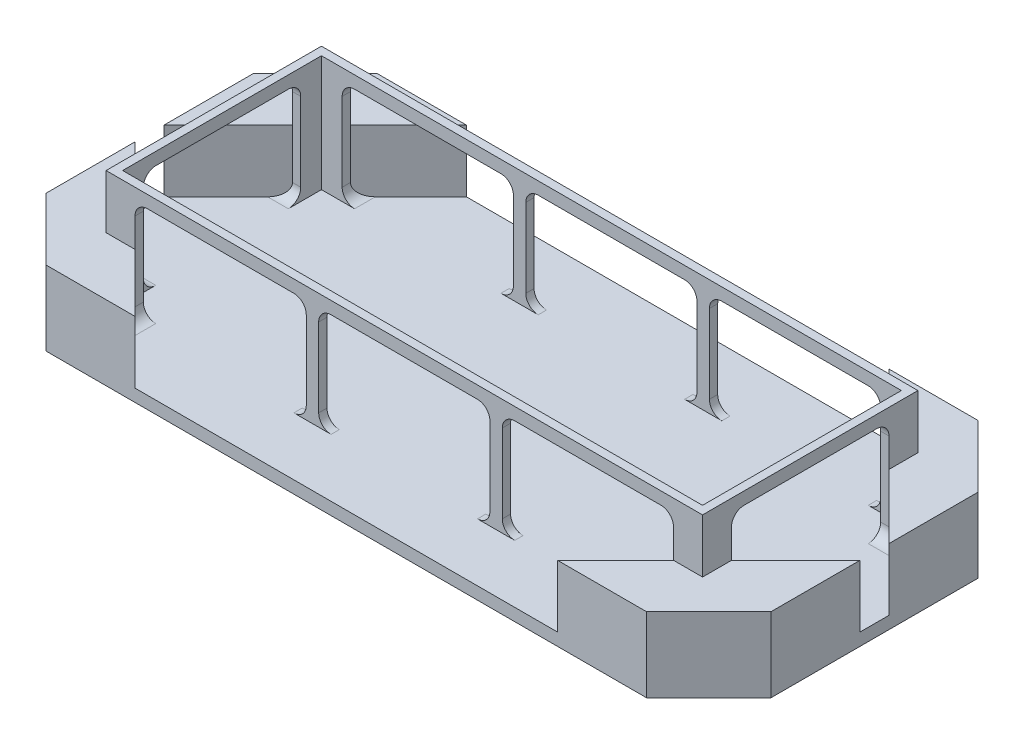
SolidWorks part; units mm, degrees
ref_plane "Спереди" through (0, 0, 0) normal (0, 0, 1) x (1, 0, 0)
ref_plane "Сверху" through (0, 0, 0) normal (0, 1, 0) x (1, 0, 0)
ref_plane "Справа" through (0, 0, 0) normal (1, 0, 0) x (0, 0, -1)
sketch "Эскиз1" plane through (0, 0, 0) normal (0, 1, 0) x (1, 0, 0)
  line L0 (-87.5, 25) -> (-72.5, 40)
  line L1 (-72.5, -40) -> (72.5, -40)
  line L2 (-87.5, -25) -> (-87.5, 25)
  line L3 (-72.5, 40) -> (72.5, 40)
  line L4 (87.5, -25) -> (87.5, 25)
  line L5 (-87.5, -40) -> (87.5, 40) construction
  line L6 (-87.5, 40) -> (87.5, -40) construction
  line L7 (-87.5, -25) -> (-72.5, -40)
  line L8 (72.5, -40) -> (87.5, -25)
  line L9 (72.5, 40) -> (87.5, 25)
  point P0 (0, 0)
  dimension "D1" = 175
  dimension "D2" = 80
extrude "Base extrusion" add sketch "Эскиз1" along normal blind 3
sketch "Эскиз2" plane through (0, 3, 0) normal (0, 1, 0) x (1, 0, 0)
  line L1 (-70, 24) -> (70, 24)
  line L2 (-70, 24) -> (-70, -24)
  line L3 (-70, -24) -> (70, -24)
  line L4 (70, 24) -> (70, -24)
  line L5 (-70, 24) -> (70, -24) construction
  line L6 (-70, -24) -> (70, 24) construction
  line L7 (-72, 26) -> (72, 26)
  line L8 (-72, 26) -> (-72, -26)
  line L9 (-72, -26) -> (72, -26)
  line L10 (72, 26) -> (72, -26)
  line L11 (-72, 26) -> (72, -26) construction
  line L12 (-72, -26) -> (72, 26) construction
  point P0 (0, 0)
  point P6 (0, 0)
  dimension "D1" = 144
  dimension "D2" = 52
  dimension "D3" = 48
  dimension "D4" = 140
extrude "Battery case extrusion" add sketch "Эскиз2" along normal blind 28
sketch "Эскиз3" plane through (0, 0, 26) normal (0, 0, 1) x (1, 0, 0)
  line L0 (-72.5, 3) -> (72.5, 3) construction
  line L1 (-65, 28) -> (-23.6667, 28)
  line L2 (-65, 28) -> (-65, 3)
  line L3 (-65, 3) -> (-23.6667, 3)
  line L4 (-23.6667, 28) -> (-23.6667, 3)
  line L5 (-72, 31) -> (-72, 3) construction
  line L6 (-72, 31) -> (72, 31) construction
  line L7 (-20.67, 28) -> (-20.67, 3)
  line L8 (-20.67, 28) -> (20.6633, 28)
  line L9 (20.6633, 28) -> (20.6633, 3)
  line L10 (-20.67, 3) -> (20.6633, 3)
  line L11 (23.66, 28) -> (23.66, 3)
  line L12 (23.66, 28) -> (64.9933, 28)
  line L13 (64.9933, 28) -> (64.9933, 3)
  line L14 (23.66, 3) -> (64.9933, 3)
  dimension "D1" = 7
  dimension "D2" = 3
  dimension "D3" = 41.3333
  dimension "D4" = 3
extrude "Battery cage cut 1" cut sketch "Эскиз3" against normal up to surface (52 mm away) up to face at (0, 17, -26)
sketch "Эскиз4" plane through (-72, 0, 0) normal (-1, 0, 0) x (0, 0, 1)
  line L0 (-25, 3) -> (25, 3) construction
  line L1 (-19, 28) -> (19, 28)
  line L2 (-19, 28) -> (-19, 3)
  line L3 (-19, 3) -> (19, 3)
  line L4 (19, 28) -> (19, 3)
  line L5 (-26, 31) -> (-26, 3) construction
  line L6 (26, 31) -> (26, 3) construction
  line L7 (-26, 31) -> (26, 31) construction
  dimension "D1" = 7
  dimension "D2" = 7
  dimension "D3" = 3
extrude "Battery cage cut 2" cut sketch "Эскиз4" against normal up to surface (144 mm away) up to face at (72, 17, 0)
ref_plane "Плоскость1" through (0, 3, 0) normal (0, 1, 0) x (1, 0, 0)
sketch "Эскиз6" plane through (0, 3, 0) normal (0, 1, 0) x (1, 0, 0)
  line L0 (-87.5, 25) -> (-72.5, 40)
  line L1 (-72.5, 40) -> (-51, 40)
  line L6 (-72, 19) -> (-65, 26) construction
  line L8 (-87.5, 25) -> (-87.5, 3.5)
  line L10 (-65, 26) -> (-72, 26) construction
  line L11 (-72, 26) -> (-72, 19) construction
  line L12 (-65, 26) -> (-72, 26)
  line L13 (-72, 26) -> (-72, 19)
  line L14 (-72, 19) -> (-87.5, 3.5)
  line L15 (-65, 26) -> (-51, 40)
  line L16 (0, 0) -> (30.1079, 0) construction
  line L18 (0, 16.1031) -> (0, 0) construction
  line L19 (65, 26) -> (72, 26)
  line L20 (72, 26) -> (72, 19)
  line L21 (72, 19) -> (87.5, 3.5)
  line L22 (87.5, 25) -> (87.5, 3.5)
  line L23 (87.5, 25) -> (72.5, 40)
  line L24 (72.5, 40) -> (51, 40)
  line L25 (65, 26) -> (51, 40)
  line L26 (0, 0) -> (-30.1079, 0) construction
  line L27 (-65, -26) -> (-72, -26)
  line L28 (-72, -26) -> (-72, -19)
  line L29 (-72, -19) -> (-87.5, -3.5)
  line L30 (-87.5, -25) -> (-87.5, -3.5)
  line L31 (-87.5, -25) -> (-72.5, -40)
  line L32 (-72.5, -40) -> (-51, -40)
  line L33 (-65, -26) -> (-51, -40)
  line L34 (65, -26) -> (51, -40)
  line L35 (72.5, -40) -> (51, -40)
  line L36 (87.5, -25) -> (72.5, -40)
  line L37 (87.5, -25) -> (87.5, -3.5)
  line L38 (72, -19) -> (87.5, -3.5)
  line L39 (72, -26) -> (72, -19)
  line L40 (65, -26) -> (72, -26)
extrude "Бобышка-Вытянуть1" add sketch "Эскиз6" along normal blind 15
fillet "Скругление1" radius 3 32 edges at (23.66, 3, -25) (-20.67, 3, -25) (20.6633, 3, -25) (-23.6667, 3, -25) (-23.6667, 28, -25) (-20.67, 28, -25) (-65, 28, -25) (-71, 28, -19) (-65, 3, -25) (-71, 3, -19) (-65, 28, 25) (-71, 28, 19) (-71, 3, 19) (-65, 3, 25) (20.6633, 28, -25) (23.66, 28, -25) (64.9933, 3, -25) (71, 3, -19) (64.9933, 28, -25) (71, 28, -19) (71, 28, 19) (71, 3, 19) (64.9933, 3, 25) (64.9933, 28, 25) (-23.6667, 3, 25) (-20.67, 3, 25) (-23.6667, 28, 25) (-20.67, 28, 25) (20.6633, 28, 25) (23.66, 28, 25) (20.6633, 3, 25) (23.66, 3, 25)
